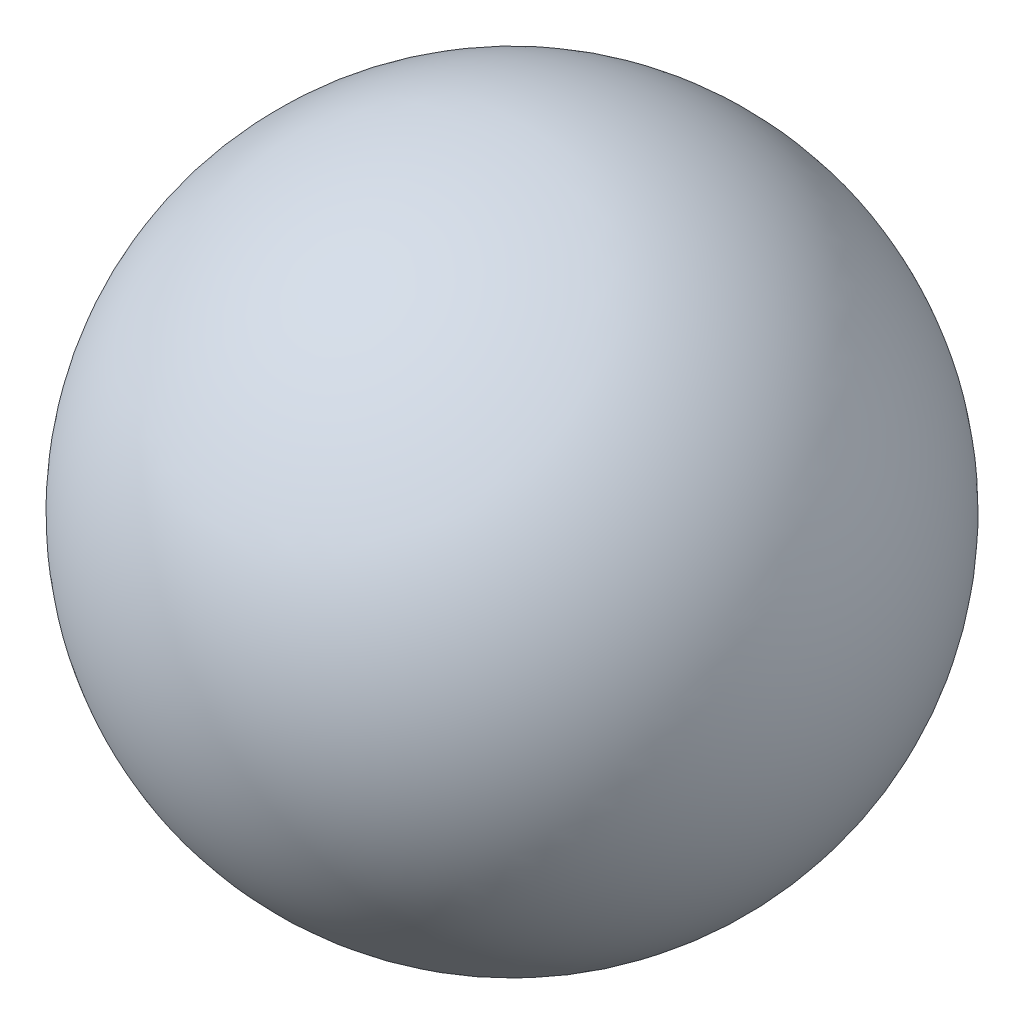
SolidWorks part; units mm, degrees
ref_plane "Front Plane" through (0, 0, 0) normal (0, 0, 1) x (1, 0, 0)
ref_plane "Top Plane" through (0, 0, 0) normal (0, 1, 0) x (1, 0, 0)
ref_plane "Right Plane" through (0, 0, 0) normal (1, 0, 0) x (0, 0, -1)
sketch "Sketch3" plane through (0, 0, 0) normal (0, 1, 0) x (1, 0, 0)
  line L0 (0, -127) -> (0, 127) construction
  arc A0 (0, 127) -> (0, -127) centre (0, 0) ccw
  dimension "D1" = 254
revolve "Revolve-Thin1" add sketch "Sketch3" angle 360 about L0
